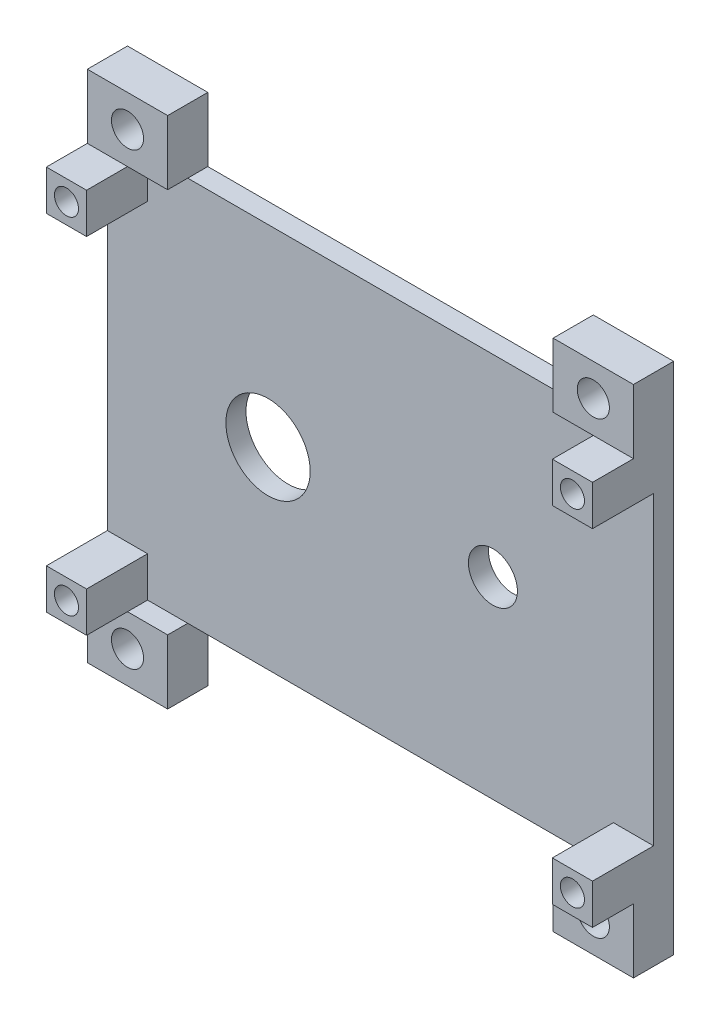
SolidWorks part; units mm, degrees
ref_plane "Přední rovina" through (0, 0, 0) normal (0, 0, 1) x (1, 0, 0)
ref_plane "Horní rovina" through (0, 0, 0) normal (0, 1, 0) x (1, 0, 0)
ref_plane "Pravá rovina" through (0, 0, 0) normal (1, 0, 0) x (0, 0, -1)
sketch "Skica1" plane through (0, 0, 0) normal (0, 0, 1) x (1, 0, 0)
  line L1 (-34, 24) -> (34, 24)
  line L2 (-34, 24) -> (-34, -24)
  line L3 (-34, -24) -> (34, -24)
  line L4 (34, 24) -> (34, -24)
  line L5 (-34, 24) -> (34, -24) construction
  line L6 (-34, -24) -> (34, 24) construction
  circle A0 centre (-14, 0) radius 5.25
  circle A1 centre (14, 0) radius 3.05
  point P0 (0, 0)
  point P8 (-34, 0)
  dimension "D2" = 10.5
  dimension "D4" = 6.1
  dimension "D1" = 48
  dimension "D3" = 20
  dimension "D5" = 28
  dimension "D6" = 68
extrude "Přidat vysunutím1" add sketch "Skica1" along normal blind 2.5
sketch "Skica2" plane through (0, 0, 2.5) normal (0, 0, 1) x (1, 0, 0)
  line L1 (-34, 24) -> (-29, 24)
  line L2 (-34, 24) -> (-34, 19)
  line L3 (-34, 19) -> (-29, 19)
  line L4 (-29, 24) -> (-29, 19)
  line L5 (34, 24) -> (29, 24)
  line L6 (34, 24) -> (34, 19)
  line L7 (34, 19) -> (29, 19)
  line L8 (29, 24) -> (29, 19)
  line L9 (34, -24) -> (29, -24)
  line L10 (34, -24) -> (34, -19)
  line L11 (34, -19) -> (29, -19)
  line L12 (29, -24) -> (29, -19)
  line L13 (-34, -24) -> (-29, -24)
  line L14 (-34, -24) -> (-34, -19)
  line L15 (-34, -19) -> (-29, -19)
  line L16 (-29, -24) -> (-29, -19)
  dimension "D1" = 5
  dimension "D3" = 5
  dimension "D5" = 5
  dimension "D8" = 5
extrude "Přidat vysunutím2" add sketch "Skica2" along normal blind 7.6
sketch "Skica3" plane through (0, 0, 10.1) normal (0, 0, 1) x (1, 0, 0)
  line L0 (-34, 24) -> (-29, 19) construction
  line L1 (-34, 19) -> (-29, 24) construction
  circle A0 centre (-31.5, 21.5) radius 1.5
  dimension "D1" = 3
extrude "Odebrat vysunutím1" cut sketch "Skica3" against normal blind 10.1
sketch "Skica8" plane through (0, 0, 10.1) normal (0, 0, 1) x (1, 0, 0)
  line L0 (29, 24) -> (34, 19) construction
  line L1 (29, 19) -> (34, 24) construction
  circle A0 centre (31.5, 21.5) radius 1.5
  dimension "D1" = 3
extrude "Odebrat vysunutím2" cut sketch "Skica8" against normal blind 10.1
sketch "Skica9" plane through (0, 0, 10.1) normal (0, 0, 1) x (1, 0, 0)
  line L0 (29, -19) -> (34, -24) construction
  line L1 (29, -24) -> (34, -19) construction
  circle A0 centre (31.5, -21.5) radius 1.5
  dimension "D1" = 3
extrude "Odebrat vysunutím3" cut sketch "Skica9" against normal blind 10.1
sketch "Skica10" plane through (0, 0, 10.1) normal (0, 0, 1) x (1, 0, 0)
  line L0 (-34, -19) -> (-29, -24) construction
  line L1 (-34, -24) -> (-29, -19) construction
  circle A0 centre (-31.5, -21.5) radius 1.5
  dimension "D1" = 3
extrude "Odebrat vysunutím4" cut sketch "Skica10" against normal blind 10.1
sketch "Skica11" plane through (0, 24, 0) normal (0, 1, 0) x (1, 0, 0)
  line L0 (29, -2.5) -> (-29, -2.5) construction
  line L1 (-34, 0) -> (-24, 0)
  line L2 (-34, 0) -> (-34, -2.5)
  line L3 (-34, -2.5) -> (-24, -2.5)
  line L4 (-24, 0) -> (-24, -2.5)
  line L6 (34, 0) -> (24, 0)
  line L7 (34, 0) -> (34, -2.5)
  line L8 (34, -2.5) -> (24, -2.5)
  line L9 (24, 0) -> (24, -2.5)
  dimension "D1" = 10
  dimension "D2" = 10
extrude "Přidat vysunutím3" add sketch "Skica11" along normal blind 8 and the other way blind 56
sketch "Skica12" plane through (0, 0, 2.5) normal (0, 0, 1) x (1, 0, 0)
  line L0 (-24, 24) -> (-24, 32) construction
  line L1 (-34, 32) -> (-24, 32) construction
  line L2 (0, -32.5458) -> (0, 31.9125) construction
  line L3 (-43.2311, 0) -> (46.4533, 0) construction
  circle A0 centre (-29, 28) radius 2
  circle A1 centre (29, 28) radius 2
  circle A2 centre (29, -28) radius 2
  circle A3 centre (-29, -28) radius 2
  dimension "D1" = 4
  dimension "D2" = 5
  dimension "D3" = 4
extrude "Odebrat vysunutím5" cut sketch "Skica12" against normal blind 8
sketch "Skica13" plane through (0, 0, 2.5) normal (0, 0, 1) x (1, 0, 0)
  line L0 (0, -32.5458) -> (0, 31.9125) construction
  line L1 (-34, 32) -> (-24, 32)
  line L2 (-34, 32) -> (-34, 24)
  line L3 (-34, 24) -> (-24, 24)
  line L4 (-24, 32) -> (-24, 24)
  line L5 (-43.2311, 0) -> (46.4533, 0) construction
  line L6 (34, 24) -> (24, 24)
  line L7 (24, 32) -> (24, 24)
  line L8 (34, 32) -> (24, 32)
  line L9 (34, 32) -> (34, 24)
  line L10 (34, -32) -> (34, -24)
  line L11 (34, -32) -> (24, -32)
  line L12 (24, -32) -> (24, -24)
  line L13 (34, -24) -> (24, -24)
  line L14 (-34, -24) -> (-24, -24)
  line L15 (-24, -32) -> (-24, -24)
  line L16 (-34, -32) -> (-24, -32)
  line L17 (-34, -32) -> (-34, -24)
  circle A0 centre (-29, 28) radius 2
  circle A1 centre (-29, 28) radius 2 construction
  circle A2 centre (29, 28) radius 2
  circle A3 centre (29, -28) radius 2
  circle A4 centre (-29, -28) radius 2
extrude "Přidat vysunutím4" add sketch "Skica13" along normal blind 2.5
